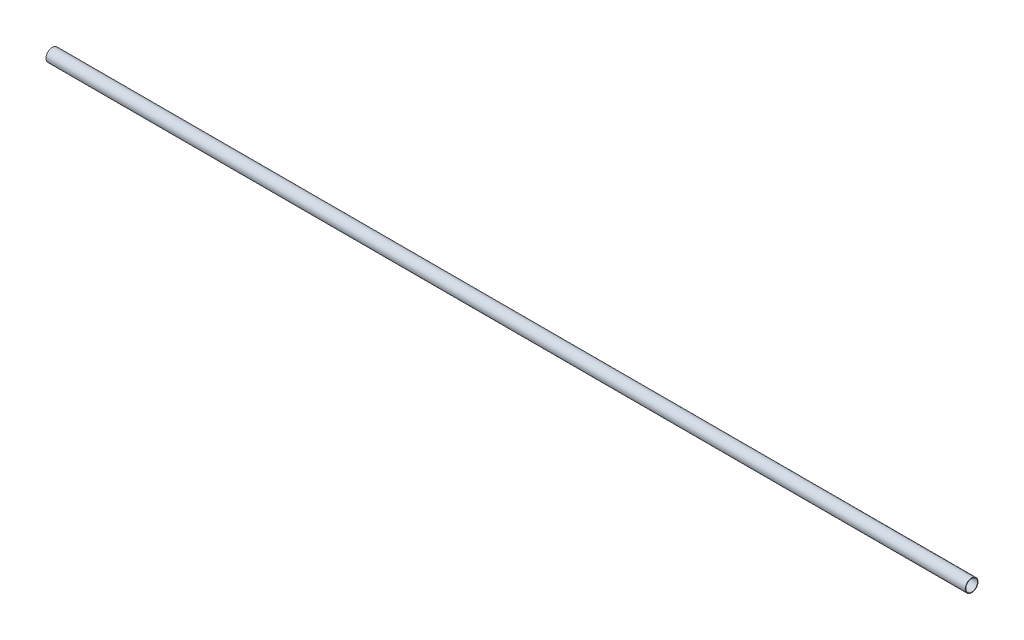
SolidWorks part; units mm, degrees
ref_plane "Front" through (0, 0, 0) normal (0, 0, 1) x (1, 0, 0)
ref_plane "Top" through (0, 0, 0) normal (0, 1, 0) x (1, 0, 0)
ref_plane "Right" through (0, 0, 0) normal (1, 0, 0) x (0, 0, -1)
sketch "Sketch1" plane through (0, 0, 0) normal (1, 0, 0) x (0, 0, -1)
  circle A0 centre (0, 0) radius 6.35
  circle A1 centre (0, 0) radius 5.842
  point P4 (6.35, 0)
  point P5 (5.842, 0)
  dimension "OD" = 12.7
  dimension "ID" = 11.684
  dimension "Wall" = 0.508
extrude "Extrude1" add sketch "Sketch1" along normal mid plane 914.4
sketch "Sketch2" plane through (0, 0, 0) normal (0, 0, 1) x (1, 0, 0)
  line L0 (-457.2, 0) -> (457.2, 0) construction
  line L1 (-457.2, 6.35) -> (-457.2, -6.35) construction
